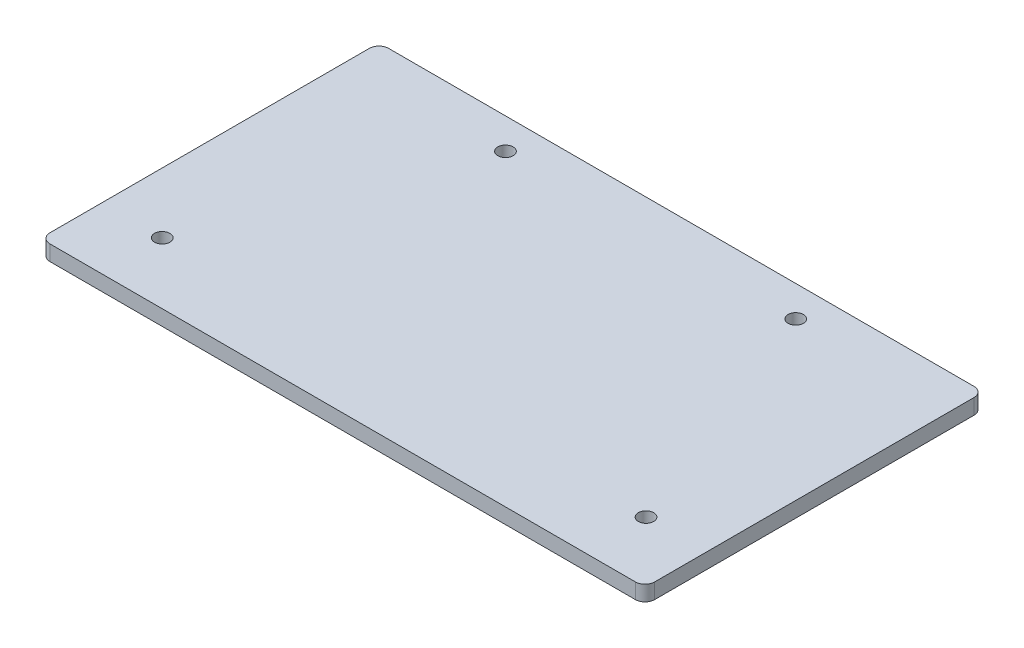
SolidWorks part; units mm, degrees
ref_plane "Front Plane" through (0, 0, 0) normal (0, 0, 1) x (1, 0, 0)
ref_plane "Top Plane" through (0, 0, 0) normal (0, 1, 0) x (1, 0, 0)
ref_plane "Right Plane" through (0, 0, 0) normal (1, 0, 0) x (0, 0, -1)
sketch "Sketch1" plane through (0, 0, 0) normal (0, 1, 0) x (1, 0, 0)
  line L0 (-62.5, -44.6) -> (62.5, -44.6) construction
  line L1 (-60.5, 0) -> (60.5, 0)
  line L2 (-62.5, -2) -> (-62.5, -68)
  line L3 (-60.5, -70) -> (60.5, -70)
  line L4 (62.5, -2) -> (62.5, -68)
  line L5 (-62.5, -12.7) -> (62.5, -12.7) construction
  arc A0 (-62.5, -68) -> (-60.5, -70) centre (-60.5, -68) ccw
  arc A1 (60.5, -70) -> (62.5, -68) centre (60.5, -68) ccw
  arc A2 (60.5, 0) -> (62.5, -2) centre (60.5, -2) cw
  arc A3 (-60.5, 0) -> (-62.5, -2) centre (-60.5, -2) ccw
  circle A4 centre (-30, -6.35) radius 1.5875
  circle A5 centre (30, -6.35) radius 1.5875
  circle A6 centre (-50, -57.3) radius 1.5875
  circle A7 centre (50, -57.3) radius 1.5875
  point P7 (-62.5, -70)
  point P12 (62.5, 0)
  point P15 (-62.5, 0)
  point P28 (0, 0)
  dimension "D3" = 2
  dimension "D8" = 3.175
  dimension "D10" = 3.175
  dimension "D11" = 12.7
  dimension "D1" = 125
  dimension "D2" = 70
  dimension "D4" = 12.7
  dimension "D5" = 25.4
  dimension "D6" = 60
  dimension "D7" = 32.5
  dimension "D9" = 6.35
  dimension "D12" = 100
  dimension "D13" = 12.5
extrude "Boss-Extrude1" add sketch "Sketch1" along normal blind 3.175
